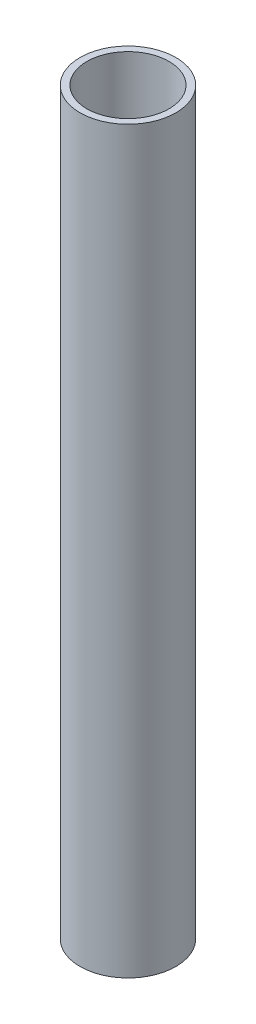
SolidWorks part; units mm, degrees
ref_plane "Front Plane" through (0, 0, 0) normal (0, 0, 1) x (1, 0, 0)
ref_plane "Top Plane" through (0, 0, 0) normal (0, 1, 0) x (1, 0, 0)
ref_plane "Right Plane" through (0, 0, 0) normal (1, 0, 0) x (0, 0, -1)
sketch "Sketch1" plane through (0, 0, 0) normal (0, 1, 0) x (1, 0, 0)
  circle A0 centre (0, 0) radius 3.5
  circle A1 centre (0, 0) radius 3
  dimension "D1" = 7
  dimension "D2" = 6
extrude "Boss-Extrude1" add sketch "Sketch1" along normal blind 54
